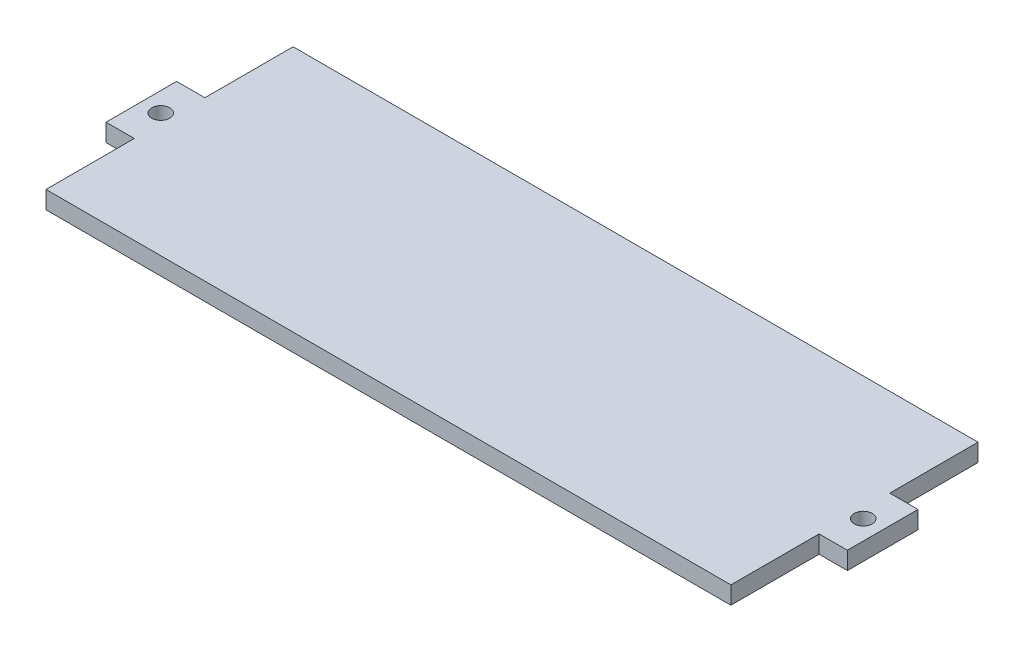
SolidWorks part; units mm, degrees
ref_plane "Front Plane" through (0, 0, 0) normal (0, 0, 1) x (1, 0, 0)
ref_plane "Top Plane" through (0, 0, 0) normal (0, 1, 0) x (1, 0, 0)
ref_plane "Right Plane" through (0, 0, 0) normal (1, 0, 0) x (0, 0, -1)
sketch "Sketch1" plane through (0, 0, 0) normal (0, 1, 0) x (1, 0, 0)
  line L0 (0, 28.575) -> (0, 44.45)
  line L1 (0, 0) -> (123.19, 0)
  line L2 (0, 0) -> (0, 15.875)
  line L3 (0, 44.45) -> (123.19, 44.45)
  line L4 (123.19, 0) -> (123.19, 15.875)
  line L5 (0, 28.575) -> (-5.08, 28.575)
  line L6 (-5.08, 22.225) -> (128.27, 22.225) construction
  line L7 (0, 15.875) -> (-5.08, 15.875)
  line L8 (-5.08, 28.575) -> (-5.08, 15.875)
  line L9 (123.19, 28.575) -> (128.27, 28.575)
  line L11 (123.19, 15.875) -> (128.27, 15.875)
  line L12 (128.27, 28.575) -> (128.27, 15.875)
  line L13 (123.19, 28.575) -> (123.19, 44.45)
  circle A0 centre (-1.5875, 22.225) radius 1.6256
  circle A1 centre (124.7775, 22.225) radius 1.6256
  dimension "D6" = 3.2512
  dimension "D7" = 3.2512
  dimension "D1" = 123.19
  dimension "D2" = 44.45
  dimension "D3" = 5.08
  dimension "D4" = 12.7
  dimension "D5" = 22.225
  dimension "D8" = 1.5875
  dimension "D9" = 1.5875
extrude "Boss-Extrude1" add sketch "Sketch1" along normal blind 3.175
